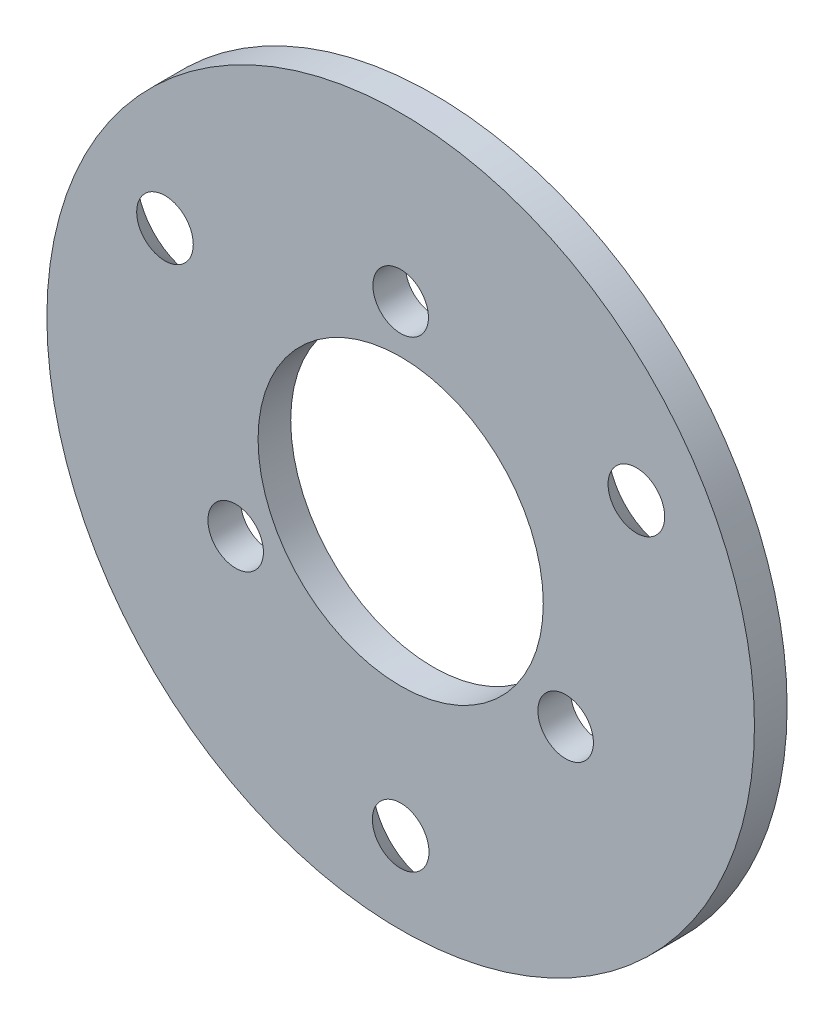
SolidWorks part; units mm, degrees
material "碳纤维"
ref_plane "前视基准面" through (0, 0, 0) normal (0, 0, 1) x (1, 0, 0)
ref_plane "上视基准面" through (0, 0, 0) normal (0, 1, 0) x (1, 0, 0)
ref_plane "右视基准面" through (0, 0, 0) normal (1, 0, 0) x (0, 0, -1)
sketch "草图1" plane through (0, 0, 0) normal (0, 0, 1) x (1, 0, 0)
  line L0 (0, 0) -> (0, 17.5) construction
  line L1 (0, 0) -> (21.6506, 12.5) construction
  circle A0 centre (0, 0) radius 17.5 construction
  circle A1 centre (0, 0) radius 25 construction
  circle A2 centre (0, 0) radius 32.5
  circle A3 centre (0, 17.5) radius 2.55
  circle A4 centre (15.1554, -8.75) radius 2.55
  circle A5 centre (-15.1554, -8.75) radius 2.55
  circle A6 centre (21.6506, 12.5) radius 2.55
  circle A7 centre (0, -25) radius 2.55
  circle A8 centre (-21.6506, 12.5) radius 2.55
  circle A9 centre (0, 0) radius 13.1
  circle A10 centre (-21.6506, 12.5) radius 4.5 construction
  circle A11 centre (0, 17.5) radius 4.5 construction
  point P14 (0, 0)
  point P21 (0, 0)
  dimension "D1" = 65
  dimension "D2" = 50
  dimension "D3" = 35
  dimension "D5" = 5.1
  dimension "D8" = 26.2
  dimension "D9" = 9
  dimension "D6" = 60
  dimension "D4" = 3
  dimension "D7" = 3
extrude "凸台-拉伸1" add sketch "草图1" along normal blind 3
hole_wizard "打孔尺寸(%根据十字)槽沉头木螺钉的类型1" positions "3D草图1" profile "草图3" countersink size "M5" standard "GB" end condition through all
sketch3d "3D草图1"
  line L3 (21.6506, 12.5, 3) -> (21.6506, 12.5, 0) construction
  line L4 (-21.6506, 12.5, 3) -> (-21.6506, 12.5, 0) construction
  line L5 (0, -25, 3) -> (0, -25, 0) construction
  point P15 (21.6506, 12.5, 0)
  point P19 (-21.6506, 12.5, 0)
  point P23 (0, -25, 0)
sketch "草图3" plane through (21.6506, 12.5, 0) normal (1, 0, 0) x (0, 1, 0)
  line L0 (0, 0) -> (0, 3)
  line L1 (0, 3) -> (2.5, 3)
  line L2 (2.5, 3) -> (2.5, 3.1)
  line L3 (2.5, 3.1) -> (5.6, 0)
  line L5 (5.6, 0) -> (0, 0)
  line L6 (-2.5, 3.1) -> (-5.6, 0) construction
  line L11 (0, -6.35) -> (0, 107.95) construction
  dimension "通孔孔直径" = 5
  dimension "通孔孔深度" = 3
  dimension "近端锥形沉头孔直径" = 11.2
  dimension "近端锥形沉头孔角度" = 90
